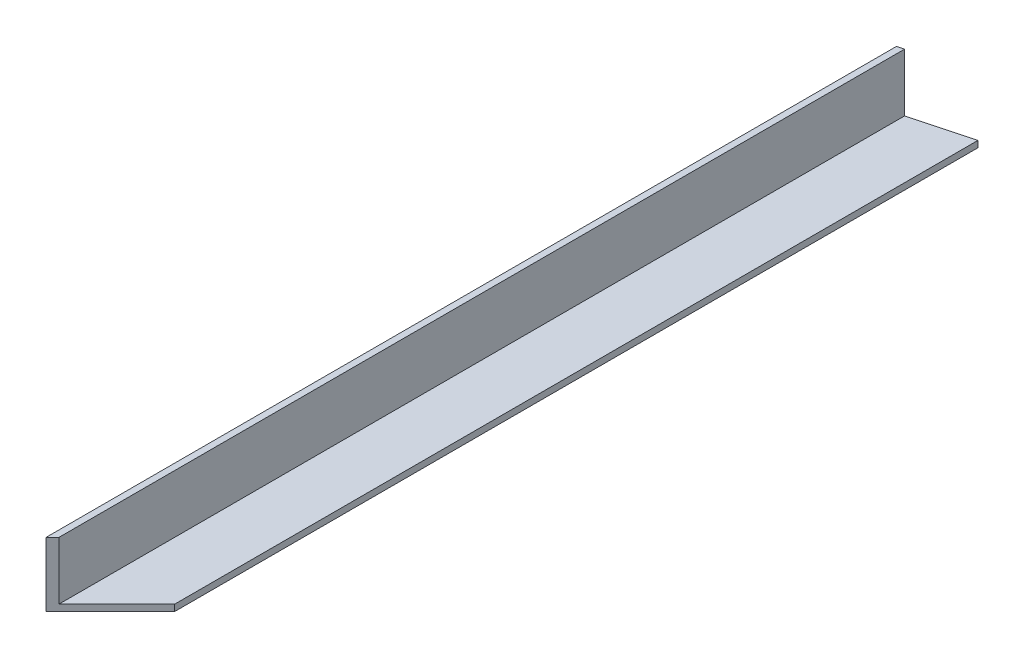
SolidWorks part; units mm, degrees
material "Acrylic (Medium-high impact)"
ref_plane "Front" through (0, 0, 0) normal (0, 0, 1) x (1, 0, 0)
ref_plane "Top" through (0, 0, 0) normal (0, 1, 0) x (1, 0, 0)
ref_plane "Right" through (0, 0, 0) normal (1, 0, 0) x (0, 0, -1)
sketch "Sketch1" plane through (0, 0, 0) normal (0, 0, 1) x (1, 0, 0)
  line L0 (0, 0) -> (0, 12.7)
  line L1 (0, 12.7) -> (1.27, 12.7)
  line L2 (1.27, 12.7) -> (1.27, 1.27)
  line L3 (1.27, 1.27) -> (12.7, 1.27)
  line L4 (12.7, 1.27) -> (12.7, 0)
  line L5 (12.7, 0) -> (0, 0)
  dimension "D1" = 12.7
  dimension "D2" = 11.43
extrude "Boss-Extrude1" add sketch "Sketch1" along normal blind 171.45
sketch "Sketch2" plane through (0, 1.27, 0) normal (0, 1, 0) x (1, 0, 0)
  line L7 (0, -168.047) -> (12.7, -171.45)
  line L8 (0, -171.45) -> (0, 0) construction
  line L9 (12.7, -171.45) -> (0, -171.45)
  line L10 (0, -171.45) -> (0, -168.047)
  line L11 (0, 0) -> (12.7, -12.7)
  line L12 (12.7, -171.45) -> (12.7, 0) construction
  line L13 (12.7, -12.7) -> (12.7, 0)
  line L14 (12.7, 0) -> (0, 0)
  dimension "D1" = 45
  dimension "D2" = 15
extrude "Cut-Extrude1" [suppressed] cut sketch "Sketch2" against normal through all and the other way through all
sketch "Sketch3" plane through (0, 1.27, 0) normal (0, 1, 0) x (1, 0, 0)
  line L0 (0, -171.45) -> (12.7, -158.75)
  line L1 (12.7, -171.45) -> (12.7, 0) construction
  line L2 (12.7, -158.75) -> (12.7, -171.45)
  line L3 (12.7, -171.45) -> (0, -171.45)
  line L4 (12.7, 0) -> (0, -3.403)
  line L5 (0, -171.45) -> (0, 0) construction
  line L6 (0, -3.403) -> (0, 0)
  line L7 (0, 0) -> (12.7, 0)
  dimension "D1" = 45
  dimension "D2" = 15
extrude "Cut-Extrude2" cut sketch "Sketch3" against normal through all and the other way through all
